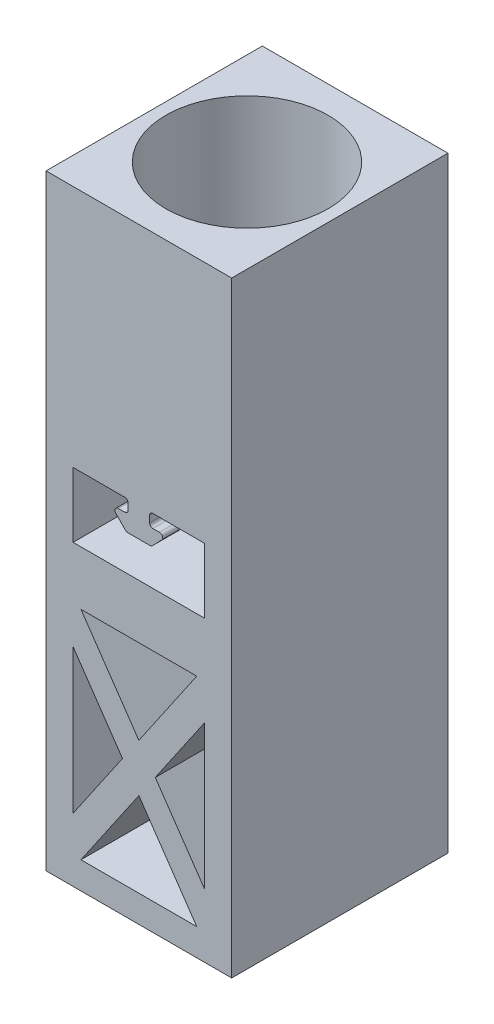
SolidWorks part; units mm, degrees
ref_plane "Front Plane" through (0, 0, 0) normal (0, 0, 1) x (1, 0, 0)
ref_plane "Top Plane" through (0, 0, 0) normal (0, 1, 0) x (1, 0, 0)
ref_plane "Right Plane" through (0, 0, 0) normal (1, 0, 0) x (0, 0, -1)
sketch "Sketch1" plane through (0, 0, 0) normal (0, 0, 1) x (1, 0, 0)
  line L0 (-21.8, -13.97) -> (21.8, -13.97) construction
  line L6 (-21.8, -13.97) -> (-21.8, 13.97)
  line L7 (-21.8, 13.97) -> (21.8, 13.97) construction
  line L8 (21.8, -13.97) -> (21.8, 13.97)
  line L9 (-21.8, 13.97) -> (21.8, -13.97) construction
  line L10 (-21.8, -13.97) -> (21.8, 13.97) construction
  line L11 (-15.45, 7.62) -> (-2.54, 7.62)
  line L12 (-15.45, 7.62) -> (-15.45, -7.62)
  line L13 (-15.45, -7.62) -> (15.45, -7.62)
  line L14 (15.45, 7.62) -> (15.45, -7.62)
  line L15 (-15.45, 7.62) -> (15.45, -7.62) construction
  line L16 (-15.45, -7.62) -> (15.45, 7.62) construction
  line L17 (-21.8, -13.97) -> (-21.8, -77.62)
  line L18 (-21.8, -77.62) -> (21.8, -77.62)
  line L19 (21.8, -13.97) -> (21.8, -77.62)
  line L20 (-21.8, -13.97) -> (21.8, -77.62) construction
  line L21 (-21.8, -77.62) -> (21.8, -13.97) construction
  line L22 (-13.6018, -20.32) -> (0, -40.1768)
  line L23 (15.45, -28.8583) -> (3.8485, -45.795)
  line L24 (13.6018, -20.32) -> (0, -40.1768)
  line L25 (0, 13.97) -> (0, -13.97) construction
  line L26 (-3.8485, -45.795) -> (-15.45, -62.7317)
  line L27 (3.8485, -45.795) -> (15.45, -62.7317)
  line L28 (0, -51.4132) -> (-13.6018, -71.27)
  line L29 (0, -51.4132) -> (13.6018, -71.27)
  line L30 (-13.6018, -20.32) -> (13.6018, -20.32)
  line L31 (15.45, -28.8583) -> (15.45, -62.7317)
  line L32 (13.6018, -71.27) -> (-13.6018, -71.27)
  line L33 (-15.45, -62.7317) -> (-15.45, -28.8583)
  line L34 (-15.45, -28.8583) -> (-3.8485, -45.795)
  line L35 (-2.54, 7.62) -> (-2.54, 4.572)
  line L36 (-2.54, 4.572) -> (-6.6548, 4.572)
  line L37 (-6.6548, 4.572) -> (-2.9337, 0.762)
  line L38 (-2.9337, 0.762) -> (2.9337, 0.762)
  line L39 (6.6548, 4.572) -> (2.9337, 0.762)
  line L40 (2.54, 4.572) -> (6.6548, 4.572)
  line L41 (2.54, 7.62) -> (2.54, 4.572)
  line L42 (2.54, 7.62) -> (15.45, 7.62)
  line L43 (-21.8, 13.97) -> (-21.8, 64.77)
  line L44 (-21.8, 64.77) -> (21.8, 64.77)
  line L45 (21.8, 64.77) -> (21.8, 13.97)
  point P0 (0, 0)
  point P8 (0, 0)
  point P9 (0, 0)
  point P31 (0, 0.762)
  dimension "D8" = 6.35
  dimension "D1" = 6.35
  dimension "D2" = 2.54
  dimension "D3" = 6.35
  dimension "D4" = 30.9
  dimension "D5" = 70
  dimension "D6" = 3.175
  dimension "D7" = 3.175
  dimension "D9" = 3.048
  dimension "D10" = 6.35
  dimension "D11" = 6.6548
  dimension "D12" = 3.175
  dimension "D13" = 3.175
  dimension "D14" = 3.175
  dimension "D15" = 6.858
  dimension "D16" = 15.24
  dimension "D17" = 50.8
extrude "Boss-Extrude1" add sketch "Sketch1" along normal blind 50.8
fillet "Fillet1" radius 0.762 8 edges at (-2.54, 7.62, 25.4) (2.54, 7.62, 25.4) (-2.9337, 0.762, 25.4) (-6.6548, 4.572, 25.4) (-2.54, 4.572, 25.4) (2.9337, 0.762, 25.4) (6.6548, 4.572, 25.4) (2.54, 4.572, 25.4)
sketch "Sketch2" plane through (0, 64.77, 0) normal (0, 1, 0) x (1, 0, 0)
  circle A0 centre (0, -25.4) radius 19.05
extrude "Cut-Extrude1" cut sketch "Sketch2" against normal blind 44.45
sketch "Sketch3" plane through (0, 64.77, 0) normal (0, 1, 0) x (1, 0, 0)
  circle A0 centre (0, -25.4) radius 12.7
extrude "Cut-Extrude2" cut sketch "Sketch3" against normal blind 66.04
